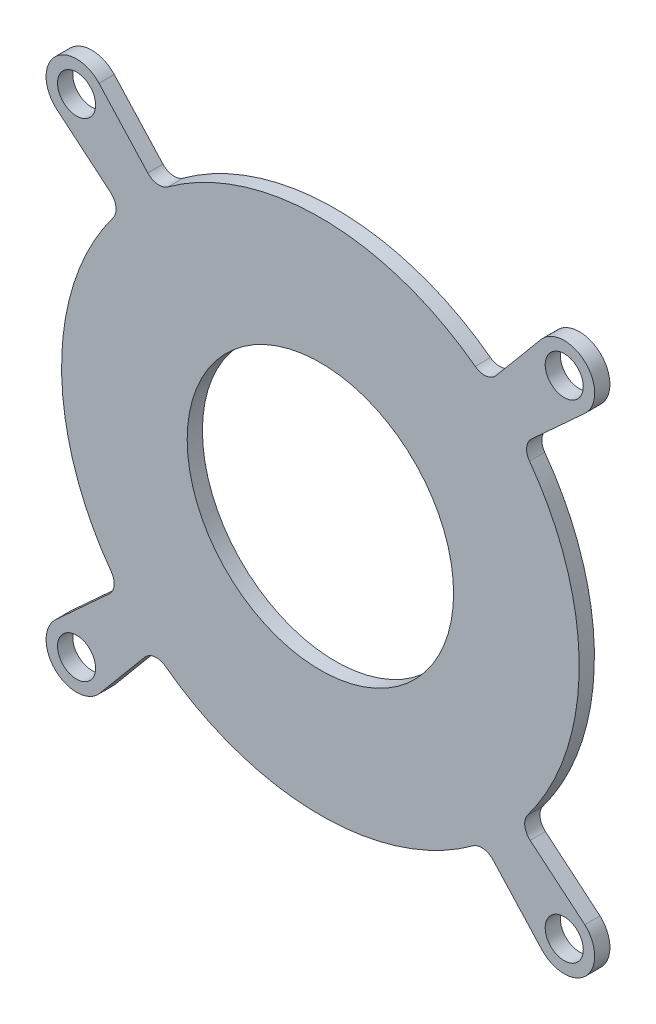
SolidWorks part; units mm, degrees
ref_plane "前视基准面" through (0, 0, 0) normal (0, 0, 1) x (1, 0, 0)
ref_plane "上视基准面" through (0, 0, 0) normal (0, 1, 0) x (1, 0, 0)
ref_plane "右视基准面" through (0, 0, 0) normal (1, 0, 0) x (0, 0, -1)
sketch "草图1" plane through (0, 0, 0) normal (0, 0, 1) x (1, 0, 0)
  line L0 (0, 0.4371) -> (28.5, 0.4371) construction
  line L105 (29.0849, -34.2991) -> (22.6815, -27.3036)
  line L106 (-34.7363, -28.6478) -> (-27.7408, -22.2444)
  line L107 (34.7363, -28.6478) -> (27.5593, -22.6385)
  line L108 (-29.0849, -34.2991) -> (-23.0756, -27.1222)
  line L109 (-29.0849, 35.1734) -> (-22.6815, 28.1779)
  line L110 (-34.7363, 29.5221) -> (-27.5593, 23.5128)
  line L111 (34.7363, 29.5221) -> (27.7408, 23.1186)
  line L112 (29.0849, 35.1734) -> (23.0756, 27.9965)
  circle A0 centre (0, 0.4371) radius 34 construction
  circle A150 centre (0, 0.4371) radius 45.305 construction
  circle A151 centre (32.0355, -31.5983) radius 2.5
  circle A152 centre (32.0355, -31.5983) radius 4 construction
  arc A153 (29.0849, -34.2991) -> (34.7363, -28.6478) centre (32.0355, -31.5983) ccw
  arc A154 (-34.7363, -28.6478) -> (-29.0849, -34.2991) centre (-32.0355, -31.5983) ccw
  circle A155 centre (-32.0355, -31.5983) radius 2.5
  arc A156 (-29.0849, 35.1734) -> (-34.7363, 29.5221) centre (-32.0355, 32.4726) ccw
  circle A157 centre (-32.0355, 32.4726) radius 2.5
  arc A158 (34.7363, 29.5221) -> (29.0849, 35.1734) centre (32.0355, 32.4726) ccw
  circle A159 centre (32.0355, 32.4726) radius 2.5
  arc A160 (-20.3454, -26.8037) -> (20.0281, -27.0378) centre (0, 0.4371) ccw
  arc A161 (27.2409, -19.9082) -> (27.475, 20.4653) centre (0, 0.4371) ccw
  arc A162 (20.3454, 27.678) -> (-20.0281, 27.9121) centre (0, 0.4371) ccw
  arc A163 (-27.2409, 20.7825) -> (-27.475, -19.591) centre (0, 0.4371) ccw
  arc A164 (-23.0756, -27.1222) -> (-20.3454, -26.8037) centre (-21.5422, -28.4061) cw
  arc A165 (22.6815, -27.3036) -> (20.0281, -27.0378) centre (21.2062, -28.654) ccw
  arc A166 (27.5593, -22.6385) -> (27.2409, -19.9082) centre (28.8433, -21.105) cw
  arc A167 (27.7408, 23.1186) -> (27.475, 20.4653) centre (29.0912, 21.6434) ccw
  arc A168 (23.0756, 27.9965) -> (20.3454, 27.678) centre (21.5422, 29.2804) cw
  arc A169 (-22.6815, 28.1779) -> (-20.0281, 27.9121) centre (-21.2062, 29.5283) ccw
  arc A170 (-27.5593, 23.5128) -> (-27.2409, 20.7825) centre (-28.8433, 21.9793) cw
  arc A171 (-27.7408, -22.2444) -> (-27.475, -19.591) centre (-29.0912, -20.7691) ccw
  circle A172 centre (0, 0.4371) radius 17.5
extrude "凸台-拉伸1" add sketch "草图1" along normal blind 2
